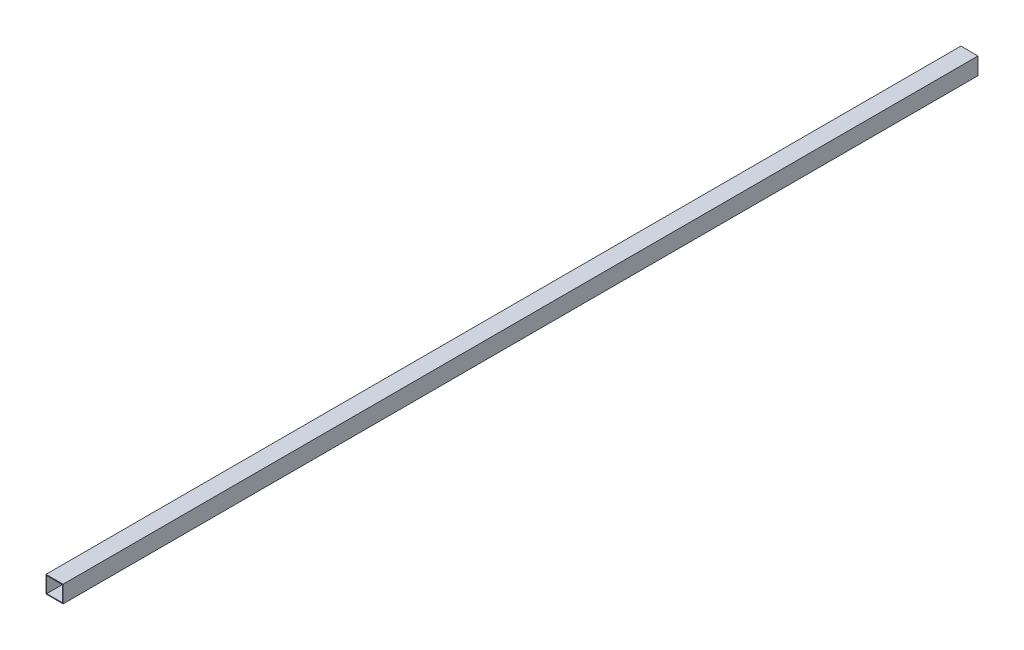
SolidWorks part; units mm, degrees
material "Plain Carbon Steel"
ref_plane "Front Plane" through (0, 0, 0) normal (0, 0, 1) x (1, 0, 0)
ref_plane "Top Plane" through (0, 0, 0) normal (0, 1, 0) x (1, 0, 0)
ref_plane "Right Plane" through (0, 0, 0) normal (1, 0, 0) x (0, 0, -1)
sketch "Sketch2" plane through (0, 0, 0) normal (0, 0, 1) x (1, 0, 0)
  line L0 (0, 19.05) -> (1.5875, 19.05) construction
  line L1 (0, 0) -> (38.1, 0)
  line L2 (0, 0) -> (0, 38.1)
  line L3 (0, 38.1) -> (38.1, 38.1)
  line L4 (38.1, 0) -> (38.1, 38.1)
  line L5 (1.5875, 1.5875) -> (36.5125, 1.5875)
  line L6 (1.5875, 1.5875) -> (1.5875, 36.5125)
  line L7 (1.5875, 36.5125) -> (36.5125, 36.5125)
  line L8 (36.5125, 1.5875) -> (36.5125, 36.5125)
  line L9 (19.05, 36.5125) -> (19.05, 38.1) construction
  line L10 (36.5125, 19.05) -> (38.1, 19.05) construction
  line L11 (19.05, 0) -> (19.05, 1.5875) construction
  dimension "D1" = 38.1
  dimension "D2" = 1.5875
  dimension "D3" = 38.1
extrude "Boss-Extrude1" add sketch "Sketch2" along normal blind 2038.35
